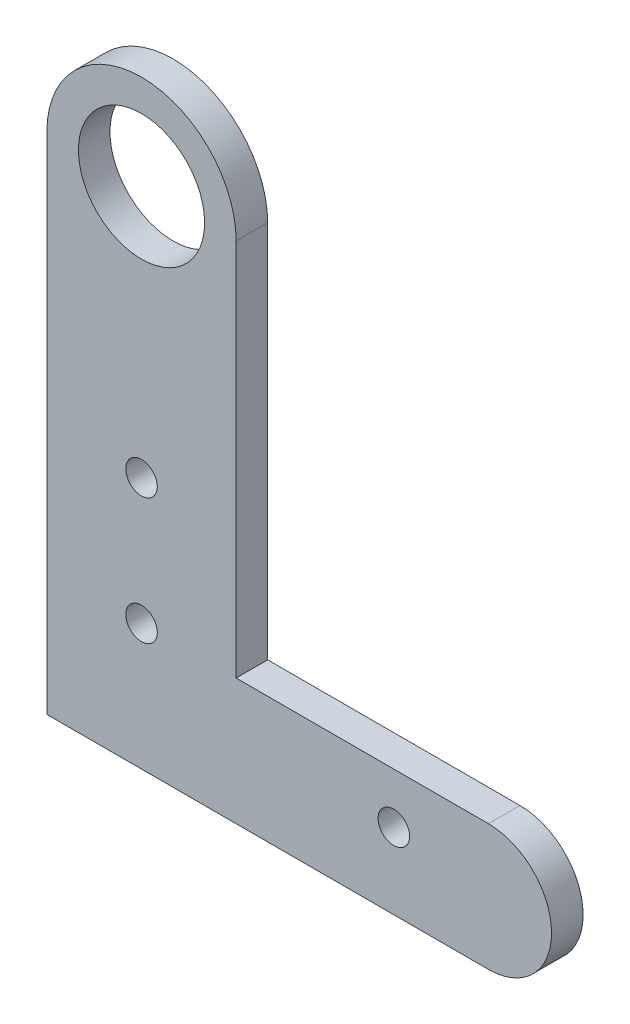
SolidWorks part; units mm, degrees
material "6063-T1"
ref_plane "Front Plane" through (0, 0, 0) normal (0, 0, 1) x (1, 0, 0)
ref_plane "Top Plane" through (0, 0, 0) normal (0, 1, 0) x (1, 0, 0)
ref_plane "Right Plane" through (0, 0, 0) normal (1, 0, 0) x (0, 0, -1)
sketch "Sketch2" plane through (0, 0, 0) normal (0, 0, 1) x (1, 0, 0)
  line L0 (0, 0) -> (70, 0)
  line L1 (70, 20) -> (30, 20)
  line L2 (30, 20) -> (30, 80)
  line L3 (0, 80) -> (0, 0)
  arc A0 (70, 0) -> (70, 20) centre (70, 10) ccw
  arc A1 (30, 80) -> (0, 80) centre (15, 80) ccw
  circle A2 centre (15, 80) radius 10
  circle A3 centre (15, 20) radius 2.5
  circle A4 centre (15, 40) radius 2.5
  circle A5 centre (55, 12) radius 2.5
  dimension "D1" = 15
  dimension "D2" = 10
  dimension "D6" = 20
  dimension "D7" = 20
  dimension "D8" = 40
  dimension "D9" = 5
  dimension "D10" = 5
  dimension "D11" = 5
  dimension "D12" = 12
  dimension "D13" = 55
  dimension "D14" = 15
  dimension "D15" = 15
  dimension "D3" = 70
  dimension "D4" = 80
  dimension "D5" = 60
extrude "Boss-Extrude1" add sketch "Sketch2" along normal blind 5
